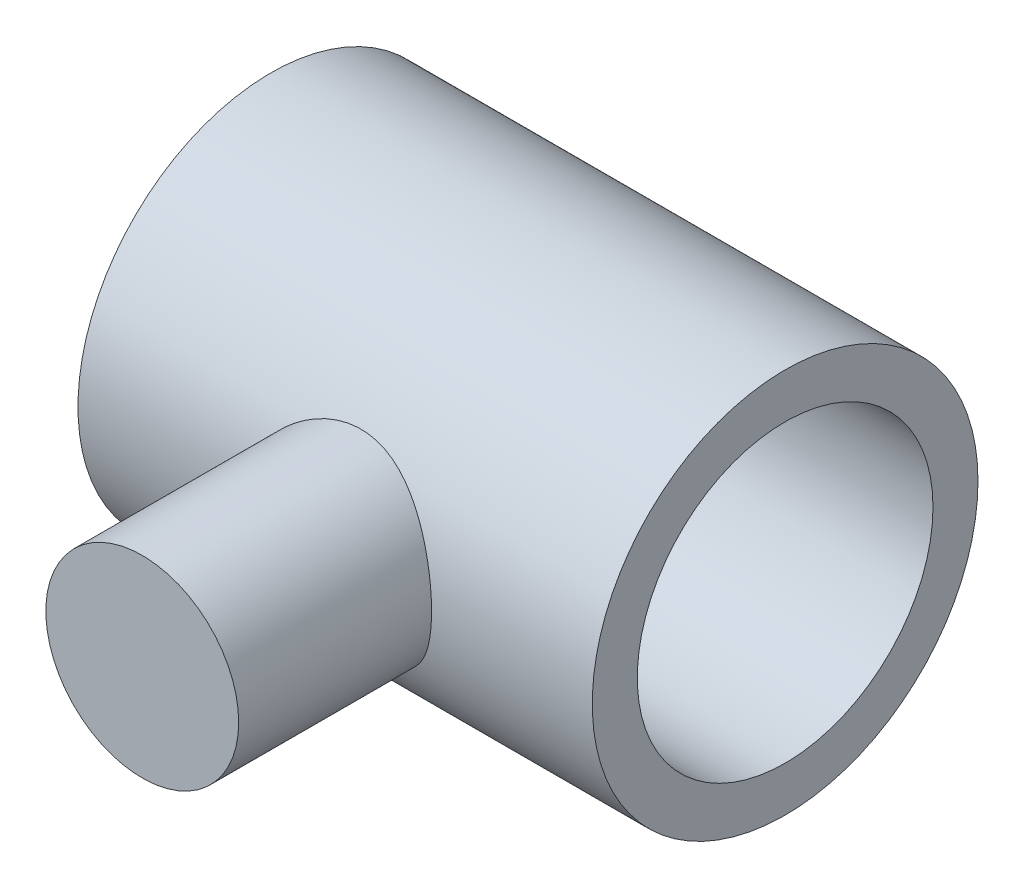
SolidWorks part; units mm, degrees
ref_plane "Front Plane" through (0, 0, 0) normal (0, 0, 1) x (1, 0, 0)
ref_plane "Top Plane" through (0, 0, 0) normal (0, 1, 0) x (1, 0, 0)
ref_plane "Right Plane" through (0, 0, 0) normal (1, 0, 0) x (0, 0, -1)
sketch "Sketch1" plane through (0, 0, 0) normal (0, 0, 1) x (1, 0, 0)
  line L0 (58.1789, 0) -> (-58.1789, 0) construction
  line L1 (20, 15) -> (-20, 15)
  line L2 (20, 11.5) -> (-20, 11.5)
  line L3 (-20, 15) -> (-20, 11.5)
  line L4 (20, 15) -> (20, 11.5)
  point P4 (0, 0)
  point P8 (0, 15)
  point P11 (0, 11.5)
  dimension "D1" = 40
  dimension "D2" = 15
  dimension "D3" = 11.5
revolve "Revolve1" add sketch "Sketch1" angle 360 about L0
ref_plane "Plane2" through (0, 0, 20) normal (0, 0, 1) x (1, 0, 0)
sketch "Sketch3" plane through (0, 0, 20) normal (0, 0, 1) x (1, 0, 0)
  circle A0 centre (0, 0) radius 7.5
  dimension "D1" = 15
extrude "Boss-Extrude1" add sketch "Sketch3" along normal blind 10 and the other way up to next
